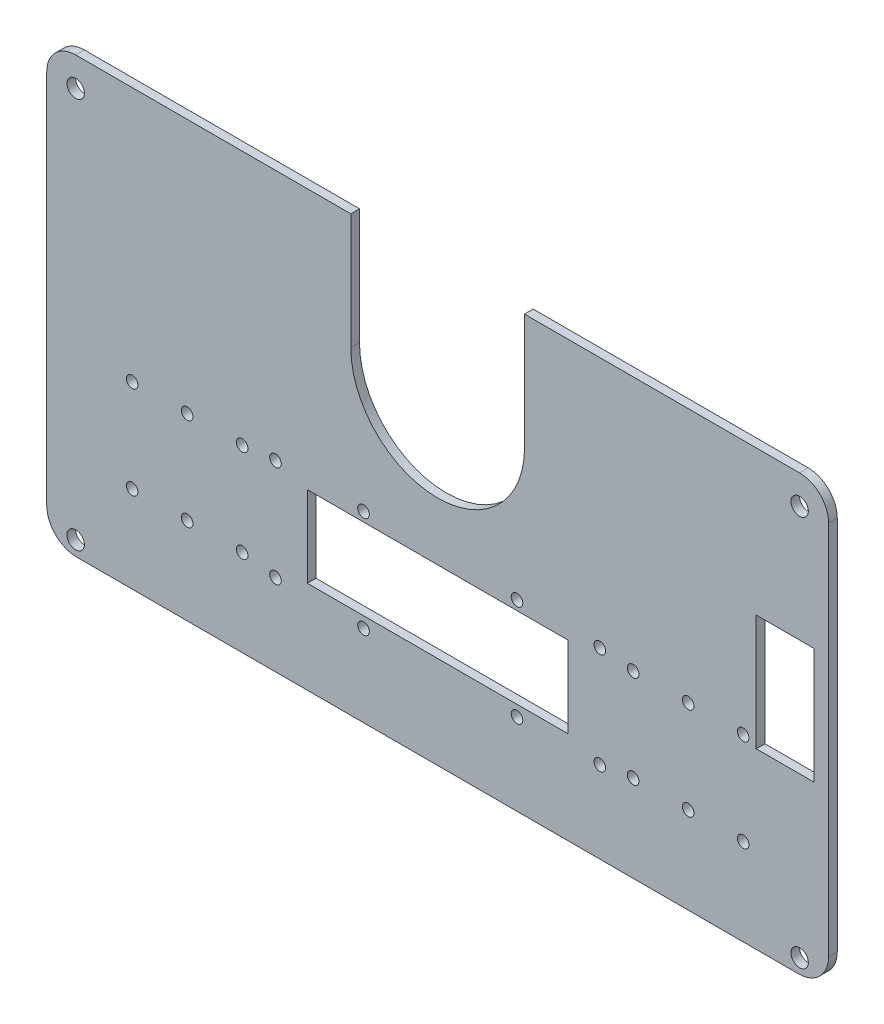
SolidWorks part; units mm, degrees
ref_plane "Front Plane" through (0, 0, 0) normal (0, 0, 1) x (1, 0, 0)
ref_plane "Top Plane" through (0, 0, 0) normal (0, 1, 0) x (1, 0, 0)
ref_plane "Right Plane" through (0, 0, 0) normal (1, 0, 0) x (0, 0, -1)
sketch "Esquisse1" plane through (0, 0, 0) normal (0, 0, 1) x (1, 0, 0)
  line L1 (10, 0) -> (105, 0)
  line L2 (0, -10) -> (0, -139.6765)
  line L3 (10.3235, -150) -> (259.6765, -150)
  line L4 (270, -10) -> (270, -139.6765)
  line L6 (105, 0) -> (105, -40)
  line L7 (165, 0) -> (165, -40)
  line L8 (165, 0) -> (260, 0)
  arc A0 (0, -10) -> (10, 0) centre (10, -10) cw
  arc A1 (260, 0) -> (270, -10) centre (260, -10) cw
  arc A2 (259.6765, -150) -> (270, -139.6765) centre (259.6765, -139.6765) ccw
  arc A3 (0, -139.6765) -> (10.3235, -150) centre (10.3235, -139.6765) ccw
  circle A4 centre (221.5127, -88) radius 2
  circle A5 centre (202.5127, -88) radius 2
  circle A6 centre (240.5127, -88) radius 2
  circle A7 centre (221.5127, -120) radius 2
  circle A8 centre (240.5127, -120) radius 2
  circle A9 centre (202.5127, -120) radius 2
  circle A10 centre (67.4873, -88) radius 2
  circle A11 centre (48.4873, -88) radius 2
  circle A12 centre (29.4873, -88) radius 2
  circle A13 centre (29.4873, -120) radius 2
  circle A14 centre (48.4873, -120) radius 2
  circle A15 centre (67.4873, -120) radius 2
  circle A16 centre (191, -121.7894) radius 2
  circle A17 centre (191, -86.7894) radius 2
  circle A18 centre (162.4, -86.7894) radius 2
  circle A19 centre (162.4, -121.7894) radius 2
  circle A20 centre (109.4, -86.7894) radius 2
  circle A21 centre (109.4, -121.7894) radius 2
  circle A22 centre (79, -86.7894) radius 2
  circle A23 centre (79, -121.7894) radius 2
  circle A24 centre (79, -86.7894) radius 2 construction
  circle A25 centre (79, -121.7894) radius 2 construction
  circle A26 centre (109.4, -121.7894) radius 2 construction
  circle A27 centre (109.4, -86.7894) radius 2 construction
  circle A28 centre (162.4, -86.7894) radius 2 construction
  circle A29 centre (162.4, -121.7894) radius 2 construction
  circle A30 centre (191, -121.7894) radius 2 construction
  circle A32 centre (191, -86.7894) radius 2 construction
  arc A33 (105, -40) -> (165, -40) centre (135, -40) ccw
  point P7 (0, 0)
  point P10 (270, 0)
  point P15 (0, -150)
  dimension "D3" = 10
  dimension "D4" = 10.3235
  dimension "D5" = 4
  dimension "D6" = 4
  dimension "D7" = 4
  dimension "D8" = 4
  dimension "D9" = 4
  dimension "D10" = 4
  dimension "D11" = 4
  dimension "D12" = 4
  dimension "D13" = 4
  dimension "D14" = 4
  dimension "D15" = 4
  dimension "D16" = 4
  dimension "D17" = 4
  dimension "D18" = 30
  dimension "D1" = 270
  dimension "D2" = 150
  dimension "D19" = 40
extrude "Boss.-Extru.1" add sketch "Esquisse1" along normal blind 3
sketch "Esquisse2" plane through (0, 0, 3) normal (0, 0, 1) x (1, 0, 0)
  line L0 (10.3235, -150) -> (259.6765, -150) construction
  line L1 (0, -10) -> (0, -139.6765) construction
  line L2 (270, -139.6765) -> (270, -10) construction
  line L4 (90, -90) -> (180, -90)
  line L5 (90, -90) -> (90, -118)
  line L6 (90, -118) -> (180, -118)
  line L7 (180, -90) -> (180, -118)
  circle A0 centre (10, -10) radius 3
  circle A1 centre (260, -10) radius 3
  circle A2 centre (260, -145) radius 3
  circle A3 centre (10, -145) radius 3
  point P20 (135, -118)
  point P21 (135, -150)
  dimension "D1" = 6
  dimension "D2" = 6
  dimension "D3" = 6
  dimension "D4" = 6
  dimension "D5" = 5
  dimension "D6" = 10
  dimension "D7" = 10
  dimension "D8" = 5
  dimension "D9" = 28
  dimension "D10" = 90
  dimension "D11" = 32
extrude "Enlèv. mat.-Extru.1" cut sketch "Esquisse2" against normal blind 3
sketch "Esquisse3" plane through (0, 0, 3) normal (0, 0, 1) x (1, 0, 0)
  line L0 (10.3235, -150) -> (259.6765, -150) construction
  line L1 (245, -50) -> (265, -50)
  line L2 (245, -50) -> (245, -90)
  line L3 (245, -90) -> (265, -90)
  line L4 (265, -50) -> (265, -90)
  line L5 (270, -139.6765) -> (270, -10) construction
  dimension "D1" = 20
  dimension "D2" = 40
  dimension "D3" = 60
  dimension "D4" = 5
extrude "Enlèv. mat.-Extru.2" cut sketch "Esquisse3" against normal blind 10
